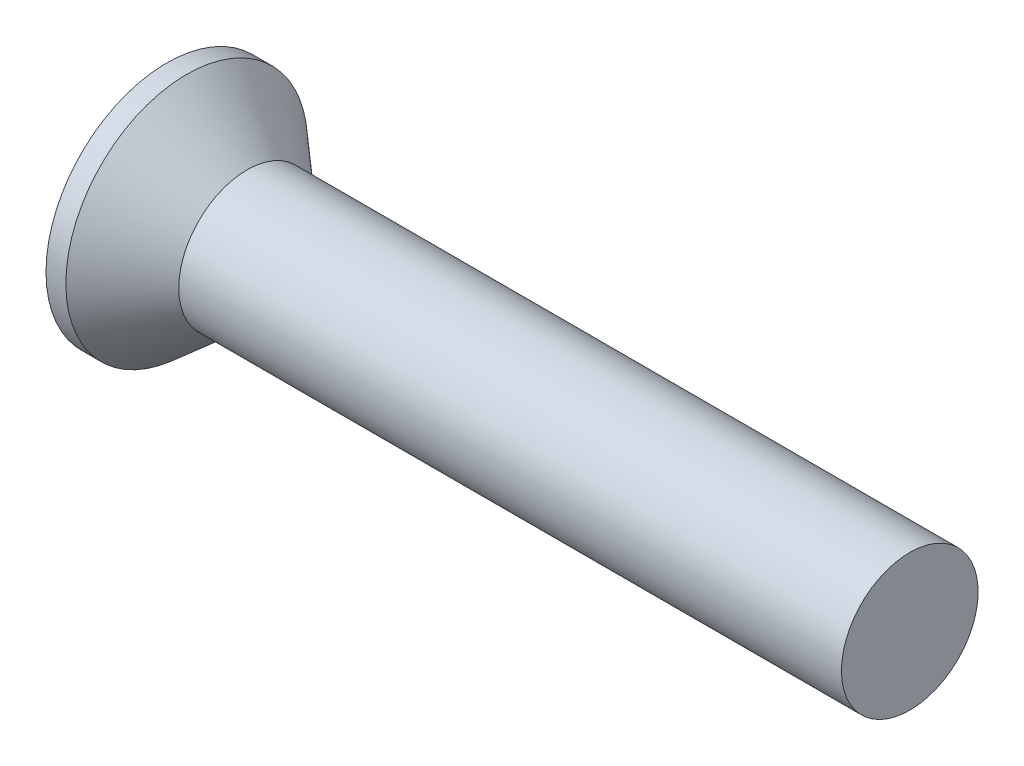
SolidWorks part; units mm, degrees
revolve "Base-Revolve" add sketch "BodySke" angle 360 about L5
sketch "BodySke" plane through (0, 0, 0) normal (0, 0, 1) x (1, 0, 0)
  line L0 (0, 0) -> (0, 3.0988)
  line L1 (0, 3.0988) -> (0.5088, 3.0988)
  line L2 (2.0574, 1.7526) -> (19.05, 1.7526)
  line L3 (19.05, 1.7526) -> (19.05, 0)
  line L4 (19.05, 0) -> (0, 0)
  line L5 (-6.35, 0) -> (82.55, 0) construction
  line L6 (2.0574, -1.7526) -> (19.05, -1.7526) construction
  line L7 (0.5088, -3.0988) -> (2.0574, -1.7526) construction
  line L8 (0.5088, 3.0988) -> (2.0574, 1.7526)
  line L9 (0, -3.0988) -> (0.5088, -3.0988) construction
  line L10 (2.8499, 3.3401) -> (2.8499, -6.1849) construction
  line L11 (0, 6.35) -> (0, -3.175) construction
  dimension "Diameter" = 3.5052
  dimension "Length" = 19.05
  dimension "Head_ht" = 2.0574
  dimension "Head_dia" = 6.1976
  dimension "Head_ang" = 82
  dimension "D6" = 0.5088
  dimension "Advance" = 0.7925
  dimension "Thread_nom" = 19.05
cosmetic thread "ThreadCosmetic" [suppressed] parameters "Thread_length"=16.2001, "Thread_minor"=2.5603
extrude "Slot" [suppressed] cut sketch "Sketch2" against normal blind 0.9652
sketch "Sketch2" plane through (0, 0, 0) normal (-1, 0, 0) x (0, 0, 1)
  line L0 (-3.0988, -0.6096) -> (3.0988, -0.6096)
  line L1 (-3.0988, -0.6096) -> (-3.0988, 0.6096)
  line L2 (3.0988, 0.6096) -> (-3.0988, 0.6096)
  line L3 (3.0988, 0.6096) -> (3.0988, -0.6096)
  dimension "Slot_width" = 1.2192
  dimension "D1" = 0.6096
  dimension "D2" = 6.1976
  dimension "D3" = 3.0988
ref_plane "Plane1" through (0, 0, 0) normal (0, 0, 1) x (1, 0, 0)
ref_plane "Plane2" through (0, 0, 0) normal (0, 1, 0) x (1, 0, 0)
ref_plane "Plane3" through (0, 0, 0) normal (1, 0, 0) x (0, 0, -1)
sketch "Sketch3" plane through (0, 0, 0) normal (-1, 0, 0) x (0, 0, 1)
  line L0 (-0.4826, 2.4765) -> (0.4826, 2.4765)
  line L1 (0.4826, 2.4765) -> (0.4826, -2.4765)
  line L2 (0.4826, -2.4765) -> (-0.4826, -2.4765)
  line L3 (-0.4826, -2.4765) -> (-0.4826, 2.4765)
  dimension "Cross_dia" = 4.953
  dimension "Cross_width" = 0.9652
  dimension "D1" = 2.4765
  dimension "D2" = 0.4826
ref_plane "Plane4" through (2.8702, 0, 0) normal (-1, 0, 0) x (0, 0, 1)
sketch "Sketch4" plane through (2.8702, 0, 0) normal (-1, 0, 0) x (0, 0, 1)
  line L0 (-0.2413, 0.2413) -> (0.2413, 0.2413)
  line L3 (0.2413, 0.2413) -> (0.2413, -0.2413)
  line L4 (0.2413, -0.2413) -> (-0.2413, -0.2413)
  line L5 (-0.2413, -0.2413) -> (-0.2413, 0.2413)
  dimension "D2" = 0.4826
  dimension "D1" = 0.4826
  dimension "D3" = 0.2413
  dimension "D4" = 0.2413
loft "Cross" cut profiles "Sketch3", "Sketch4"
pattern_circular "CirPattern1" count 2 every 90 about axis through (0, 0, 0) along (1, 0, 0) of "Cross"
sketch "ThdSchSke" plane through (0, 0, 0) normal (0, 0, 1) x (1, 0, 0)
  line L0 (2.8499, -1.2802) -> (2.5191, -1.7526)
  line L1 (2.8499, -1.2802) -> (3.1807, -1.7526)
  line L2 (3.1807, -1.7526) -> (3.1807, -2.1907)
  line L3 (-3.175, 0) -> (5.1513, 0) construction
  line L5 (3.1807, -2.1907) -> (2.5191, -2.1907)
  line L6 (2.5191, -2.1907) -> (2.5191, -1.7526)
  line L7 (0, 3.0988) -> (0, -3.0988) construction
  dimension "Diameter" = 3.5052
  dimension "Thread_minor" = 2.5603
  dimension "Start" = 2.8499
revolve "ThreadSchematic" [suppressed] cut sketch "ThdSchSke" angle 360 about L3
pattern_linear "ThdSchPat" [suppressed]
equation "\"D1@Sketch3\" = \"Cross_dia@Sketch3\" / 2"
equation "\"D2@Sketch3\" = \"Cross_width@Sketch3\" / 2"
equation "\"D1@Sketch4\" = \"Cross_width@Sketch3\" *.5"
equation "\"D2@Sketch4\" = \"D1@Sketch4\""
equation "\"D4@Sketch4\" = \"D2@Sketch4\" / 2"
equation "\"D3@Sketch4\" = \"D1@Sketch4\" / 2"
equation "\"D1@Sketch2\" = \"Slot_width@Sketch2\" / 2"
equation "\"D2@Sketch2\" = \"Head_dia@BodySke\""
equation "\"D3@Sketch2\" = \"D2@Sketch2\" / 2"
equation "\"Thread_length@ThreadCosmetic\" = ((sgn( (\"Length@BodySke\" - \"Advance@BodySke\" - \"Head_ht@BodySke\" ) - \"Thread_nom@BodySke\" )-1)*( (\"Length@BodySke\" - \"Advance@BodySke\" - \"Head_ht@BodySke\" ) - \"Thread_nom@BodySke\" ))/-2+ \"Thread_nom@BodySke\""
equation "\"Thread_minor@ThdSchSke\" = \"Thread_minor@ThreadCosmetic\""
equation "\"Diameter@ThdSchSke\" = \"Diameter@BodySke\""
equation "\"Overcut@ThdSchSke\" = \"Diameter@BodySke\" * 1.25"
equation "\"Start@ThdSchSke\" = 0.000001 + \"Length@BodySke\" - \"Thread_length@ThreadCosmetic\"  '---Countersunk---"
equation "\"Num_threads@ThdSchPat\" = int( \"Thread_length@ThreadCosmetic\" / \"Advance@BodySke\" + 0.999 )  + 1"
equation "\"Advance@ThdSchPat\" = \"Thread_length@ThreadCosmetic\" /  (\"Num_threads@ThdSchPat\" - 1) 'relax it"
